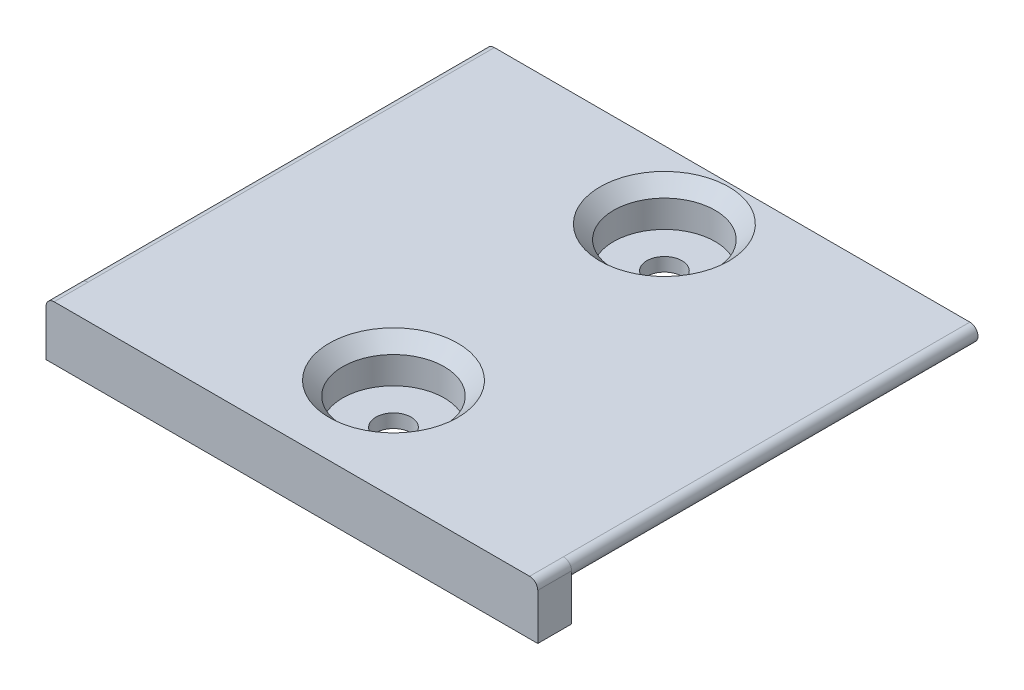
SolidWorks part; units mm, degrees
ref_plane "Спереди" through (0, 0, 0) normal (0, 0, 1) x (1, 0, 0)
ref_plane "Сверху" through (0, 0, 0) normal (0, 1, 0) x (1, 0, 0)
ref_plane "Справа" through (0, 0, 0) normal (1, 0, 0) x (0, 0, -1)
other "Configuration Table"
sketch "Эскиз1" plane through (0, 0, 0) normal (0, 0, 1) x (1, 0, 0)
  line L0 (-30, 0) -> (30, 0)
  line L1 (30, 0) -> (38, 8)
  line L2 (38, 8) -> (-38, 8)
  line L3 (-38, 8) -> (-30, 0)
  line L4 (0, 0) -> (-182.4234, 0) construction
  point P4 (0, 0)
  dimension "D1" = 45
  dimension "D2" = 60
  dimension "D3" = 8
extrude "Бобышка-Вытянуть1" add sketch "Эскиз1" along normal blind 60
sketch "Эскиз2" plane through (0, 8, 0) normal (0, 1, 0) x (1, 0, 0)
  line L0 (0, 0) -> (0, -60) construction
  line L1 (38, 0) -> (-38, 0) construction
  line L2 (38, -60) -> (-38, -60) construction
  circle A0 centre (0, -10) radius 2.6
  circle A1 centre (0, -50) radius 2.6
  dimension "D1" = 5.2
  dimension "D2" = 40
  dimension "D3" = 10
extrude "Вырез-Вытянуть1" cut sketch "Эскиз2" against normal up to surface (8 mm away) up to face at (0, 0, 30)
sketch "Эскиз3" plane through (0, 8, 0) normal (0, 1, 0) x (1, 0, 0)
  circle A0 centre (0, -10) radius 7.5
  circle A1 centre (0, -50) radius 7.5
  dimension "D1" = 15
extrude "Вырез-Вытянуть2" cut sketch "Эскиз3" against normal offset from surface (6 mm away) 2 up to face at (-2.6, 0, 10)
fillet "Скругление2" radius 1.2 2 edges at (-38, 8, 30) (38, 8, 30)
sketch "Эскиз4" plane through (0, 0, 60) normal (0, 0, 1) x (1, 0, 0)
  line L0 (-30, 0) -> (30, 0) construction
  line L1 (-36.3029, 8) -> (36.3029, 8)
  line L2 (-36.3029, 8) -> (-36.3029, 0)
  line L3 (-36.3029, 0) -> (36.3029, 0)
  line L4 (36.3029, 8) -> (36.3029, 0)
  line L5 (35.1029, 8) -> (-35.1029, 8) construction
  arc A0 (-35.1029, 8) -> (-35.9515, 5.9515) centre (-35.1029, 6.8) ccw construction
  arc A1 (35.9515, 5.9515) -> (35.1029, 8) centre (35.1029, 6.8) ccw construction
extrude "Бобышка-Вытянуть2" add sketch "Эскиз4" along normal blind 5
fillet "Скругление3" radius 1.2 2 edges at (36.3029, 8, 62.5) (-36.3029, 8, 62.5)
chamfer "Фаска3" distance 2 angle 45 2 edges at (-7.5, 8, 10) (-7.5, 8, 50)
